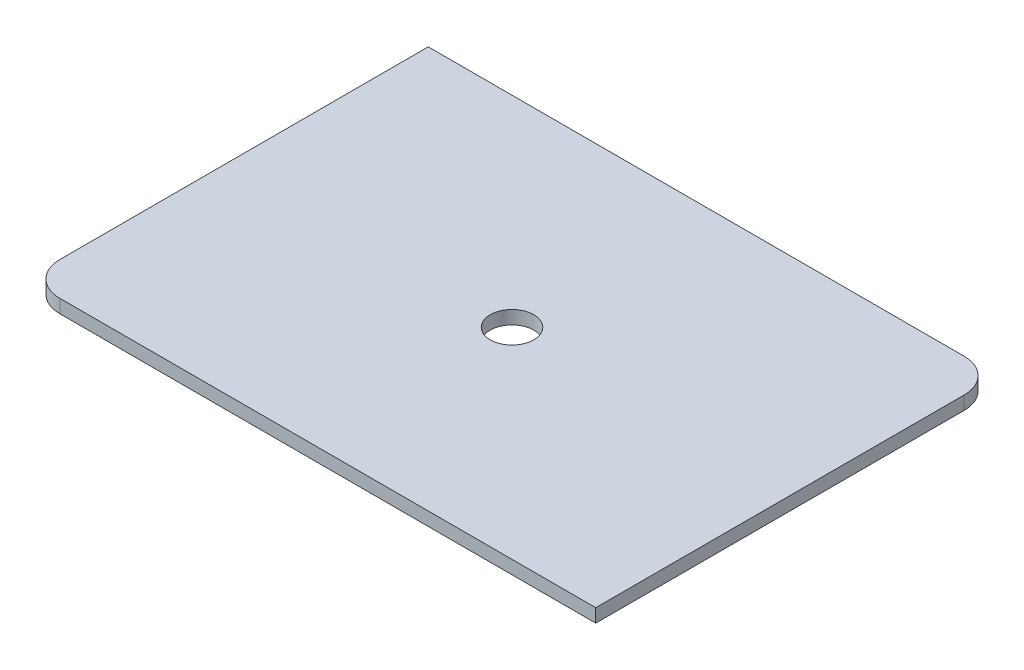
SolidWorks part; units mm, degrees
ref_plane "Front Plane" through (0, 0, 0) normal (0, 0, 1) x (1, 0, 0)
ref_plane "Top Plane" through (0, 0, 0) normal (0, 1, 0) x (1, 0, 0)
ref_plane "Right Plane" through (0, 0, 0) normal (1, 0, 0) x (0, 0, -1)
sketch "Sketch2" plane through (0, 0, 0) normal (0, 1, 0) x (1, 0, 0)
  line L1 (75, 60) -> (-85, 60)
  line L2 (85, 50) -> (85, -60)
  line L3 (85, -60) -> (-75, -60)
  line L4 (-85, 60) -> (-85, -50)
  line L5 (85, 60) -> (-85, -60) construction
  line L6 (85, -60) -> (-85, 60) construction
  arc A0 (75, 60) -> (85, 50) centre (75, 50) cw
  arc A1 (-75, -60) -> (-85, -50) centre (-75, -50) cw
  point P0 (0, 0)
  dimension "D3" = 10
  dimension "D1" = 170
  dimension "D2" = 120
extrude "Boss-Extrude1" add sketch "Sketch2" against normal blind 4
sketch "Sketch3" plane through (0, 0, 0) normal (0, 1, 0) x (1, 0, 0)
  circle A0 centre (0, 0) radius 6.5
  dimension "D1" = 13
extrude "Cut-Extrude1" cut sketch "Sketch3" against normal up to next
